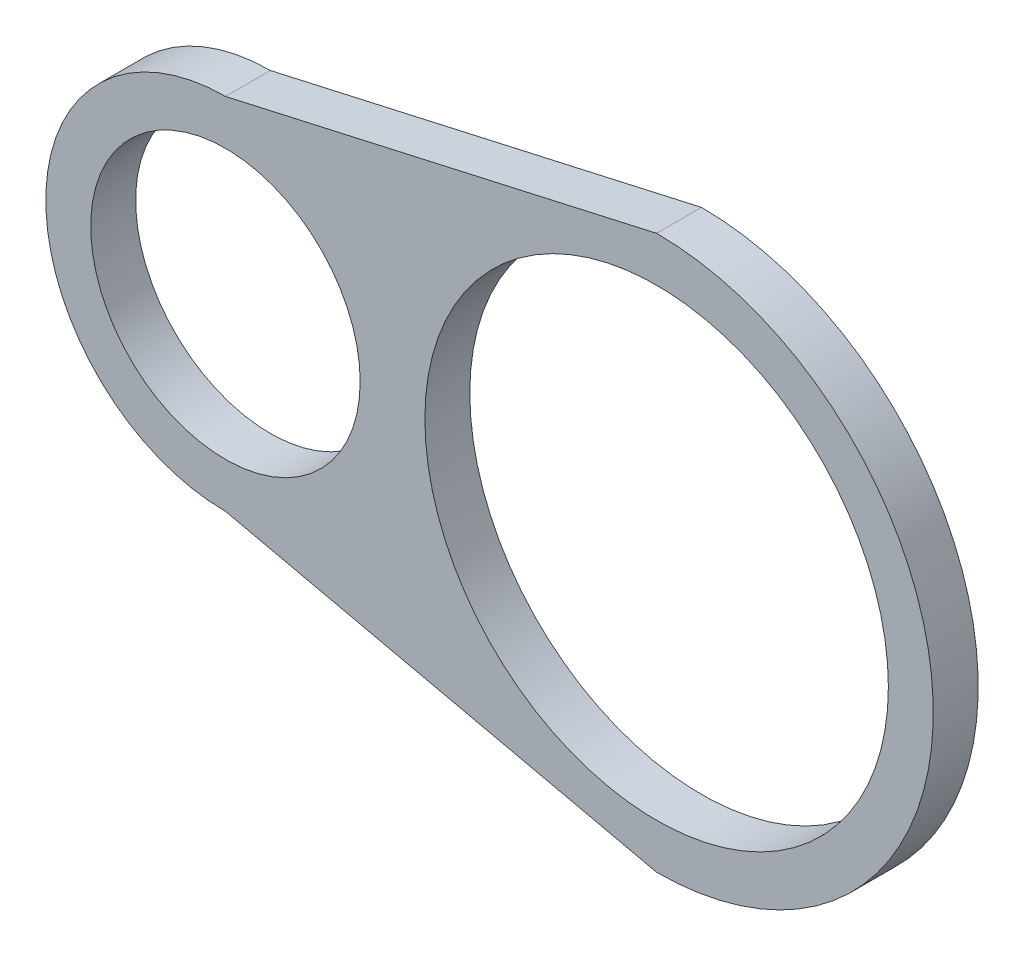
SolidWorks part; units mm, degrees
ref_plane "Plano frontal" through (0, 0, 0) normal (0, 0, 1) x (1, 0, 0)
ref_plane "Plano superior" through (0, 0, 0) normal (0, 1, 0) x (1, 0, 0)
ref_plane "Plano direito" through (0, 0, 0) normal (1, 0, 0) x (0, 0, -1)
sketch "Esboço2" plane through (0, 0, 0) normal (0, 0, 1) x (1, 0, 0)
  line L0 (-24, 0) -> (24, 0) construction
  circle A0 centre (24, 0) radius 25.8
  circle A1 centre (-24, 0) radius 15
  arc A2 (-5.715, 8.103) -> (-5.715, -8.103) centre (-24, 0) ccw
  arc A3 (-5.715, -8.103) -> (-5.715, 8.103) centre (24, 0) ccw
  circle A4 centre (24, 0) radius 30.8 construction
  circle A5 centre (-24, 0) radius 20 construction
  spline S0 degree 1 poles (24, 30.8) (-24, 20) knots 0 0 1 1
  spline S1 degree 1 poles (-24, -20) (24, -30.8) knots 0 0 1 1
  point P4 (0, 0)
  dimension "D1" = 5
extrude "Ressalto-extrusão1" add sketch "Esboço2" along normal blind 5
